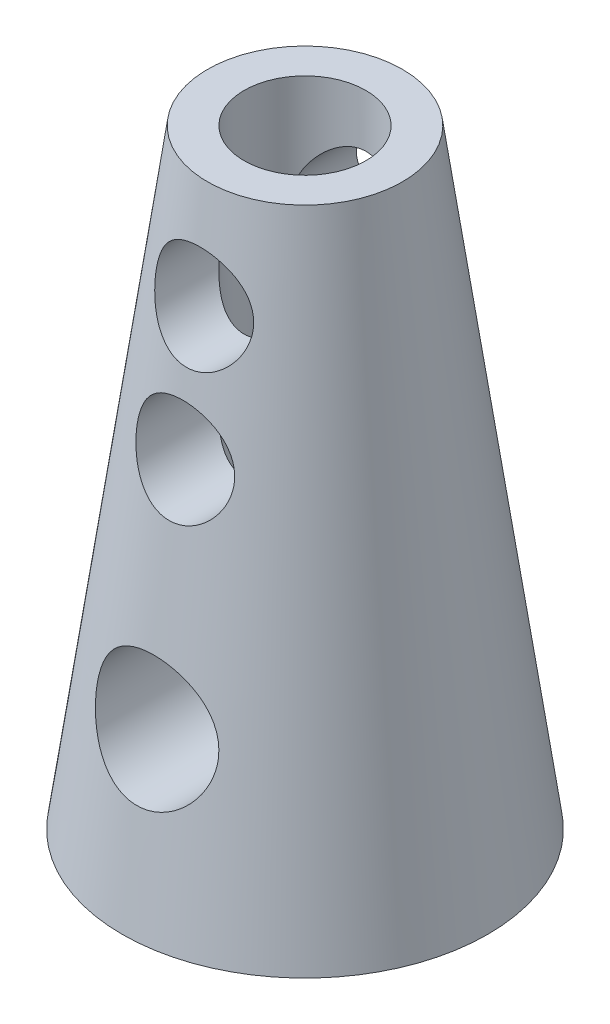
SolidWorks part; units mm, degrees
ref_plane "Plan de face" through (0, 0, 0) normal (0, 0, 1) x (1, 0, 0)
ref_plane "Plan de dessus" through (0, 0, 0) normal (0, 1, 0) x (1, 0, 0)
ref_plane "Plan de droite" through (0, 0, 0) normal (1, 0, 0) x (0, 0, -1)
sketch "Esquisse1" plane through (0, 0, 0) normal (0, 0, 1) x (1, 0, 0)
  line L0 (0, -24.3006) -> (0, 48.979) construction
  line L1 (5, 25.6994) -> (5, -24.3006)
  line L2 (5, -24.3006) -> (15, -24.3006)
  line L3 (15, -24.3006) -> (8, 25.6994)
  line L4 (8, 25.6994) -> (5, 25.6994)
  dimension "D1" = 5
  dimension "D2" = 10
  dimension "D3" = 3
  dimension "D4" = 50
revolve "Révolution1" add sketch "Esquisse1" angle 360 about L0
sketch "Esquisse2" plane through (0, 0, 0) normal (0, 0, 1) x (1, 0, 0)
  circle A0 centre (0, 17.3705) radius 4
  circle A1 centre (0, 7.197) radius 4
  circle A2 centre (0, -10.7411) radius 5
  dimension "D1" = 8
  dimension "D2" = 8
  dimension "D3" = 10
extrude "Enlèv. mat.-Extru.1" cut sketch "Esquisse2" against normal up to surface and the other way up to surface up to face at (0, 25.6994, -8) other way up to face at (0, 25.6994, -8)
